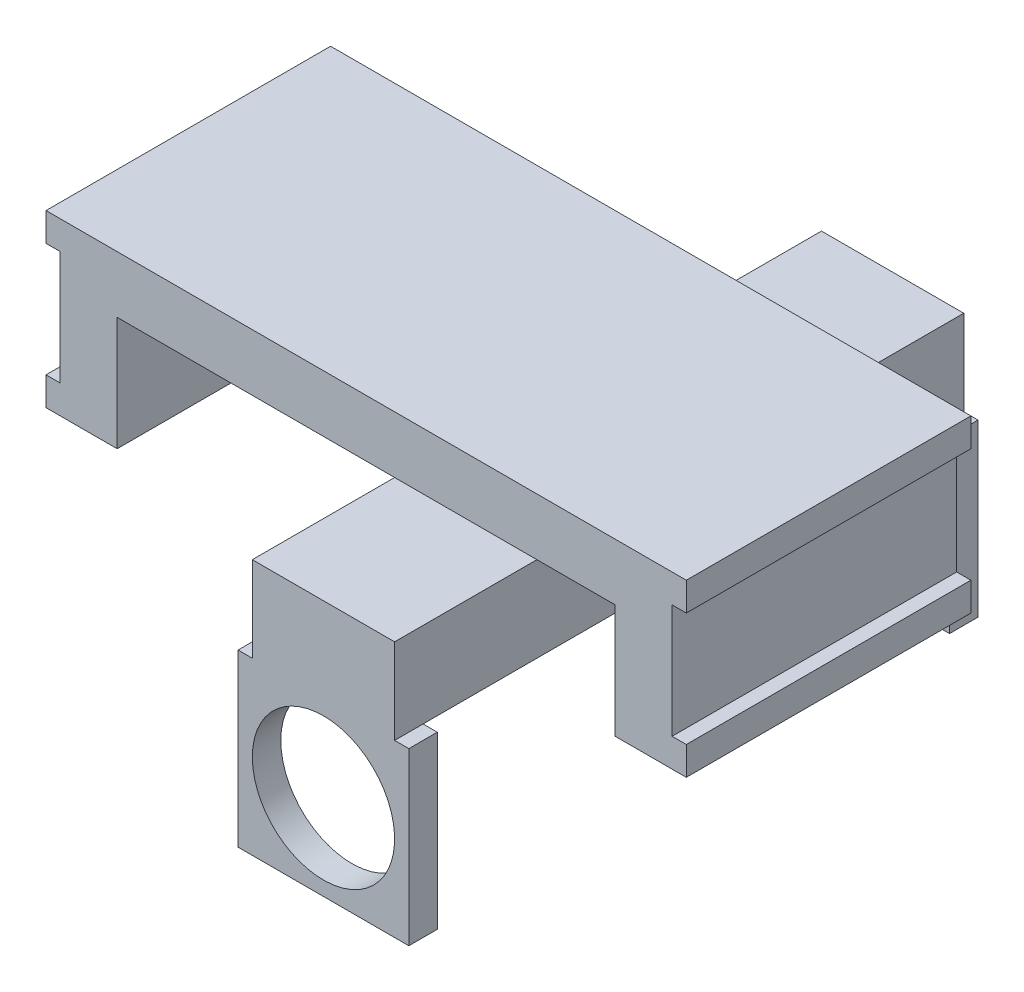
SolidWorks part; units mm, degrees
ref_plane "Front Plane" through (0, 0, 0) normal (0, 0, 1) x (1, 0, 0)
ref_plane "Top Plane" through (0, 0, 0) normal (0, 1, 0) x (1, 0, 0)
ref_plane "Right Plane" through (0, 0, 0) normal (1, 0, 0) x (0, 0, -1)
sketch "Sketch1" plane through (0, 0, 0) normal (0, 1, 0) x (1, 0, 0)
  line L1 (-28.575, -12.7) -> (28.575, -12.7)
  line L2 (-28.575, -12.7) -> (-28.575, 12.7)
  line L3 (-28.575, 12.7) -> (28.575, 12.7)
  line L4 (28.575, -12.7) -> (28.575, 12.7)
  line L5 (-28.575, -12.7) -> (28.575, 12.7) construction
  line L6 (-28.575, 12.7) -> (28.575, -12.7) construction
  point P0 (0, 0)
  dimension "D1" = 25.4
  dimension "D2" = 57.15
extrude "Boss-Extrude1" add sketch "Sketch1" along normal blind 15.24
sketch "Sketch2" plane through (0, 0, 0) normal (0, -1, 0) x (1, 0, 0)
  line L0 (-28.575, 12.7) -> (28.575, 12.7) construction
  line L1 (-22.225, 12.7) -> (22.225, 12.7)
  line L2 (-22.225, 12.7) -> (-22.225, -12.7)
  line L3 (-22.225, -12.7) -> (22.225, -12.7)
  line L4 (22.225, 12.7) -> (22.225, -12.7)
  line L5 (28.575, -12.7) -> (-28.575, -12.7) construction
  line L6 (0, 12.7) -> (0, 0) construction
  line L7 (-28.575, -12.7) -> (-28.575, 12.7) construction
  point P8 (0, 12.7)
  dimension "D1" = 6.35
extrude "Cut-Extrude1" cut sketch "Sketch2" against normal blind 10.16
sketch "Sketch3" plane through (0, 0, 12.7) normal (0, 0, 1) x (1, 0, 0)
  line L0 (-28.575, 15.24) -> (-28.575, 0) construction
  line L1 (-28.575, 12.7) -> (-27.305, 12.7)
  line L2 (-28.575, 12.7) -> (-28.575, 2.54)
  line L3 (-28.575, 2.54) -> (-27.305, 2.54)
  line L4 (-27.305, 12.7) -> (-27.305, 2.54)
  line L5 (28.575, 15.24) -> (28.575, 0) construction
  line L6 (28.575, 12.7) -> (27.305, 12.7)
  line L7 (28.575, 12.7) -> (28.575, 2.54)
  line L8 (28.575, 2.54) -> (27.305, 2.54)
  line L9 (27.305, 12.7) -> (27.305, 2.54)
  line L10 (22.225, 10.16) -> (-22.225, 10.16) construction
  dimension "D1" = 1.27
  dimension "D2" = 10.16
  dimension "D3" = 2.54
extrude "Cut-Extrude2" cut sketch "Sketch3" against normal through all
sketch "Sketch4" plane through (0, 0, 0) normal (0, -1, 0) x (1, 0, 0)
  line L1 (2.54, -25.4) -> (15.24, -25.4)
  line L2 (2.54, -25.4) -> (2.54, 25.4)
  line L3 (2.54, 25.4) -> (15.24, 25.4)
  line L4 (15.24, -25.4) -> (15.24, 25.4)
  dimension "D1" = 2.54
  dimension "D2" = 50.8
  dimension "D3" = 12.7
  dimension "D4" = 25.4
extrude "Boss-Extrude2" add sketch "Sketch4" along normal blind 7.62 from surface at -10.16 starting at face at (0, 10.16, 0)
sketch "Sketch6" plane through (0, 0, -25.4) normal (0, 0, -1) x (-1, 0, 0)
  line L0 (-16.51, 2.54) -> (-16.51, -12.7)
  line L1 (-2.54, 2.54) -> (-15.24, 2.54) construction
  line L2 (-16.51, -12.7) -> (-1.27, -12.7)
  line L3 (-1.27, -12.7) -> (-1.27, 2.54)
  line L4 (-1.27, 2.54) -> (-16.51, 2.54)
  line L5 (-16.51, 2.54) -> (-1.27, -12.7) construction
  line L6 (-2.54, 2.54) -> (-15.24, 2.54) construction
  circle A0 centre (-8.89, -5.08) radius 6.35
  point P9 (-8.89, 2.54)
  dimension "D1" = 12.7
  dimension "D2" = 15.24
  dimension "D3" = 15.24
extrude "Boss-Extrude3" add sketch "Sketch6" against normal blind 2.54
mirror "Mirror1" about plane through (0, 0, 0) normal (0, 0, 1) of "Boss-Extrude3"
